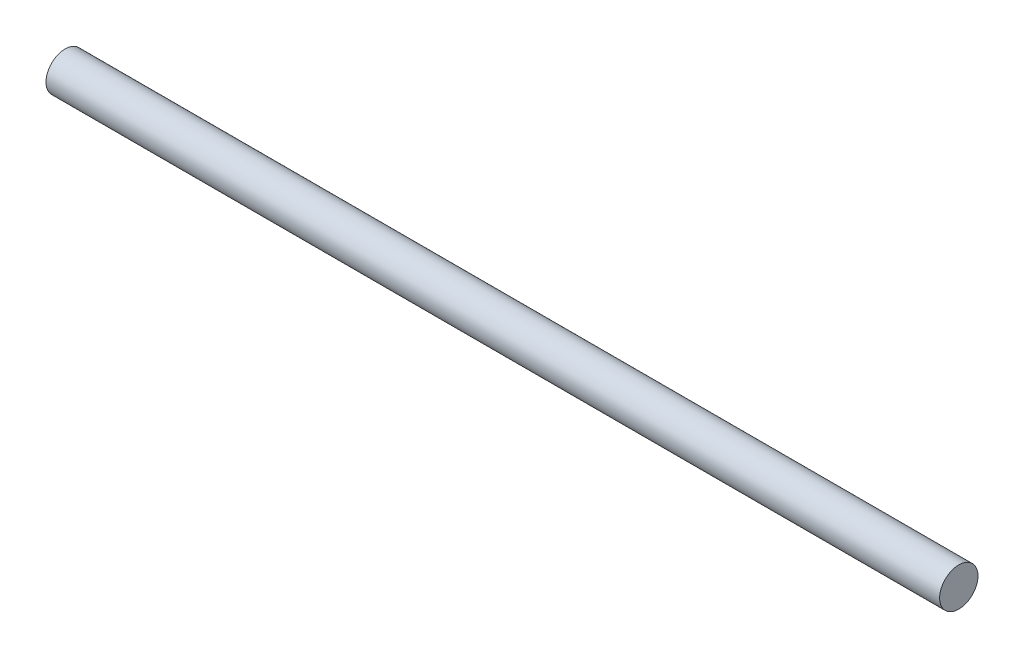
SolidWorks part; units mm, degrees
ref_plane "Front" through (0, 0, 0) normal (0, 0, 1) x (1, 0, 0)
ref_plane "Top" through (0, 0, 0) normal (0, 1, 0) x (1, 0, 0)
ref_plane "Right" through (0, 0, 0) normal (1, 0, 0) x (0, 0, -1)
sketch "Sketch2" plane through (0, 0, 0) normal (1, 0, 0) x (0, 0, -1)
  circle A0 centre (0, 0) radius 2.25
  dimension "D1" = 4.5
extrude "Base-Extrude" add sketch "Sketch2" along normal blind 104.775
